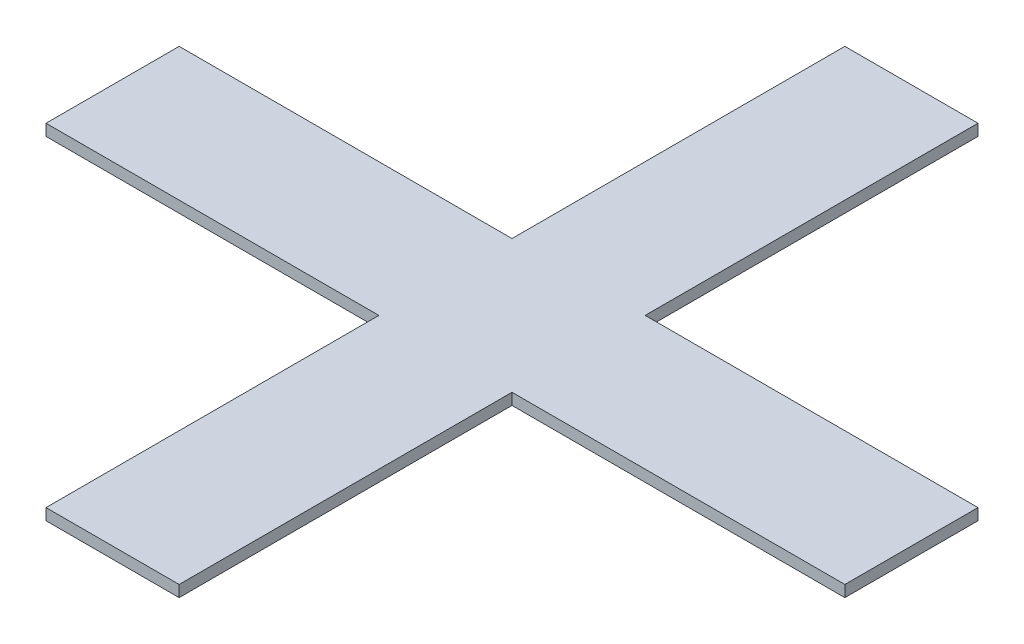
SolidWorks part; units mm, degrees
ref_plane "Front Plane" through (0, 0, 0) normal (0, 0, 1) x (1, 0, 0)
ref_plane "Top Plane" through (0, 0, 0) normal (0, 1, 0) x (1, 0, 0)
ref_plane "Right Plane" through (0, 0, 0) normal (1, 0, 0) x (0, 0, -1)
sketch "Sketch1" plane through (0, 0, 0) normal (0, 1, 0) x (1, 0, 0)
  line L0 (-30, 180) -> (-30, 30)
  line L1 (-30, 30) -> (-180, 30)
  line L2 (-180, 30) -> (-180, 0)
  line L3 (-30, 180) -> (0, 180)
  line L4 (0, 180) -> (0, 0) construction
  line L5 (0, 0) -> (-180, 0) construction
  line L6 (180, 30) -> (30, 30)
  line L7 (30, 30) -> (30, 180)
  line L8 (30, 180) -> (0, 180)
  line L9 (180, 30) -> (180, 0)
  line L10 (30, -180) -> (30, -30)
  line L11 (30, -30) -> (180, -30)
  line L12 (180, -30) -> (180, 0)
  line L13 (30, -180) -> (0, -180)
  line L14 (-180, -30) -> (-30, -30)
  line L15 (-30, -30) -> (-30, -180)
  line L16 (-30, -180) -> (0, -180)
  line L17 (-180, -30) -> (-180, 0)
  point P5 (20, -20)
  point P25 (0, 0)
  dimension "D1" = 4
  dimension "D2" = 60
  dimension "D3" = 150
extrude "Boss-Extrude1" add sketch "Sketch1" along normal blind 5.15 contours L17 L14 L15 L16 L13 L10 L11 L12 L9 L6 L7 L8 L3 L0 L1 L2
